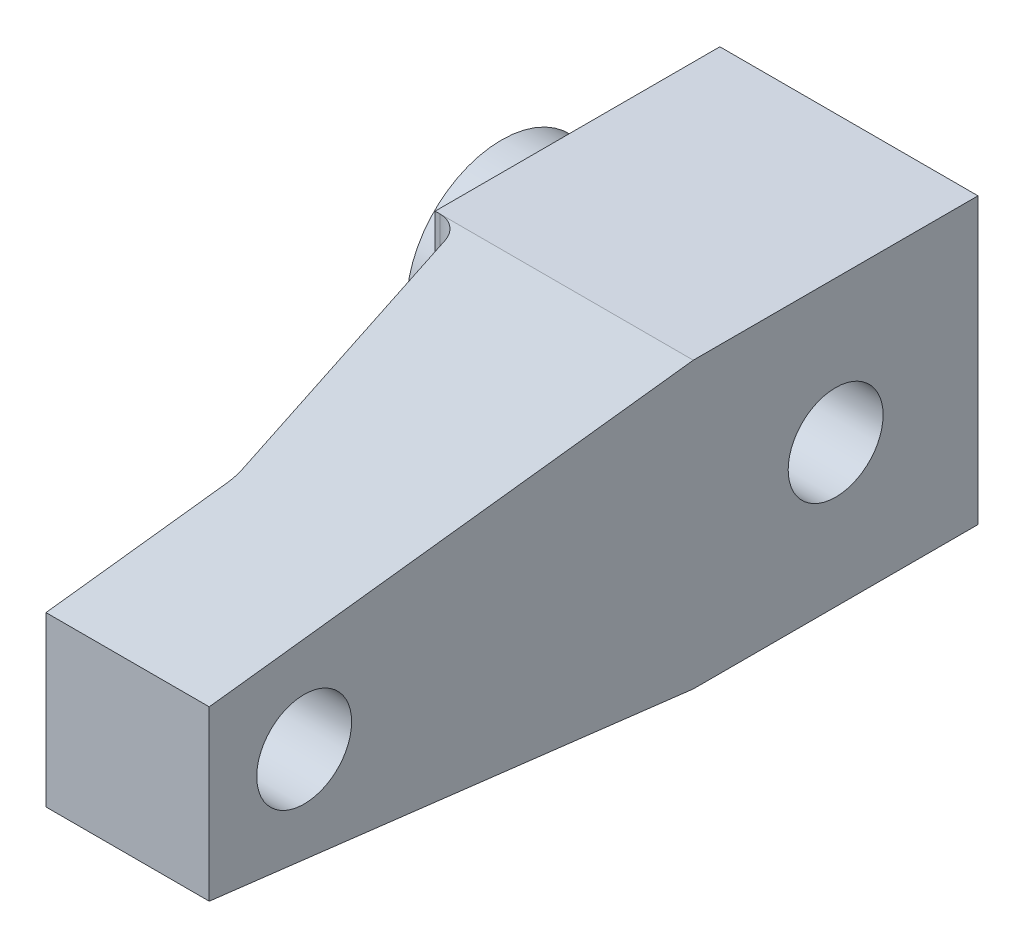
SolidWorks part; units mm, degrees
material "Custom Plastic"
ref_plane "Front Plane" through (0, 0, 0) normal (0, 0, 1) x (1, 0, 0)
ref_plane "Top Plane" through (0, 0, 0) normal (0, 1, 0) x (1, 0, 0)
ref_plane "Right Plane" through (0, 0, 0) normal (1, 0, 0) x (0, 0, -1)
sketch "Sketch1" plane through (0, 0, 0) normal (1, 0, 0) x (0, 0, -1)
  line L0 (4.7625, 4.7625) -> (4.7625, -4.7625)
  line L1 (4.7625, -4.7625) -> (-4.7625, -4.7625)
  line L2 (-4.7625, -4.7625) -> (-20.955, -2.8162)
  line L3 (-20.955, -2.8162) -> (-20.955, 2.8162)
  line L4 (4.7625, 4.7625) -> (-4.7625, 4.7625)
  line L5 (-4.7625, 4.7625) -> (-20.955, 2.8162)
  circle A0 centre (0, 0) radius 1.5875
  circle A1 centre (-17.78, 0) radius 1.5875
  dimension "D1" = 3.175
  dimension "D7" = 3.175
  dimension "D2" = 4.7625
  dimension "D3" = 4.7625
  dimension "D4" = 9.525
  dimension "D5" = 4.7625
  dimension "D6" = 25.7175
  dimension "D8" = 3.175
  dimension "D9" = 3.175
  dimension "D10" = 3.175
extrude "Boss-Extrude1" add sketch "Sketch1" along normal blind 8.636
sketch "Sketch2" plane through (0, 0, 0) normal (0, 1, 0) x (1, 0, 0)
  line L0 (0.9406, -5.3696) -> (3.1038, -14.3106)
  line L1 (8.636, -4.7625) -> (0, -4.7625) construction
  line L2 (3.175, -14.9079) -> (3.175, -20.955)
  line L3 (8.636, -20.955) -> (0, -20.955) construction
  line L4 (3.175, -20.955) -> (0, -20.955)
  line L5 (0, -4.7625) -> (0, -20.955) construction
  line L6 (0, -20.955) -> (0, -4.7625)
  line L7 (0, -4.7625) -> (0.1691, -4.7625)
  arc A0 (0.9406, -5.3696) -> (0.1691, -4.7625) centre (0.1691, -5.5563) ccw
  arc A1 (3.175, -14.9079) -> (3.1038, -14.3106) centre (0.635, -14.9079) ccw
  point P13 (0.7937, -4.7625)
  point P16 (3.175, -14.605)
  dimension "D4" = 0.7937
  dimension "D5" = 2.54
  dimension "D1" = 6.35
  dimension "D2" = 3.175
  dimension "D3" = 0.7937
extrude "Cut-Extrude1" cut sketch "Sketch2" against normal through all both and the other way through all
sketch "Sketch3" plane through (0, 0, 0) normal (-1, 0, 0) x (0, 0, 1)
  circle A0 centre (0, 0) radius 3.175
  circle A1 centre (0, 0) radius 1.5875
  circle A2 centre (0, 0) radius 1.5875 construction
  dimension "D1" = 6.35
extrude "Boss-Extrude2" add sketch "Sketch3" along normal blind 2.54
equation "\"D3@Sketch1\"=\"D4@Sketch1\"/2"
equation "\"D2@Sketch1\"=\"D3@Sketch1\""
equation "\"D5@Sketch1\"=\"D3@Sketch1\""
equation "\"D10@Sketch1\"=\"D9@Sketch1\""
